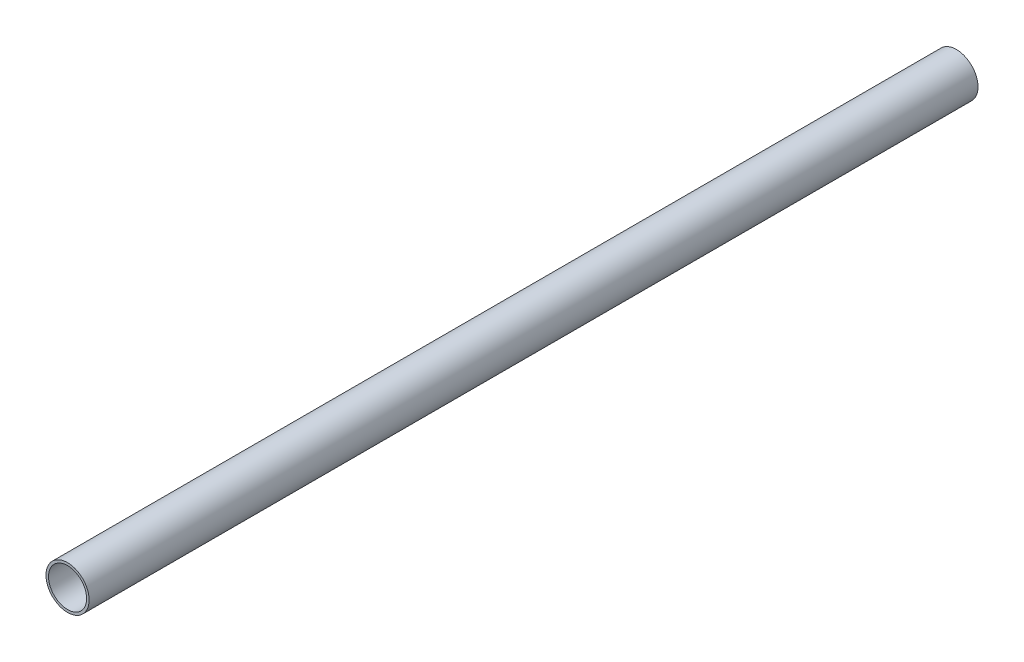
SolidWorks part; units mm, degrees
ref_plane "Front Plane" through (0, 0, 0) normal (0, 0, 1) x (1, 0, 0)
ref_plane "Top Plane" through (0, 0, 0) normal (0, 1, 0) x (1, 0, 0)
ref_plane "Right Plane" through (0, 0, 0) normal (1, 0, 0) x (0, 0, -1)
sketch "Sketch1" plane through (0, 0, 0) normal (0, 0, 1) x (1, 0, 0)
  circle A0 centre (0, 0) radius 15
  circle A1 centre (0, 0) radius 17
  dimension "D1" = 34
  dimension "D2" = 30
extrude "Boss-Extrude1" add sketch "Sketch1" along normal blind 700
